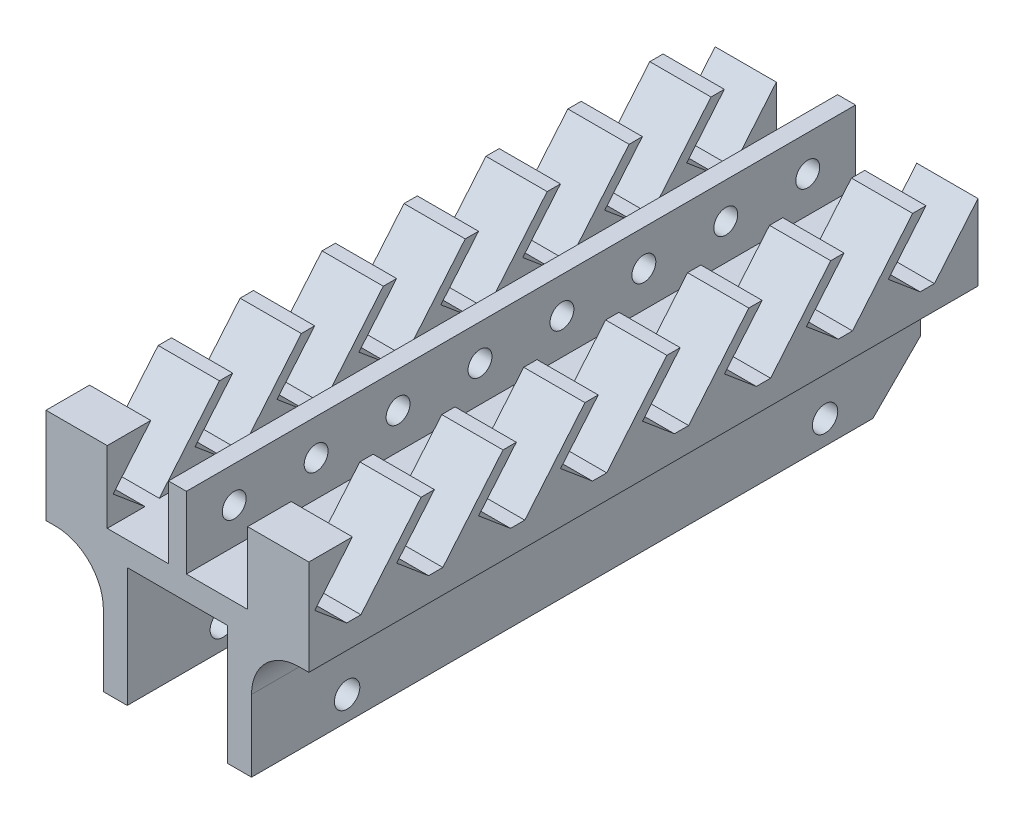
SolidWorks part; units mm, degrees
ref_plane "Front Plane" through (0, 0, 0) normal (0, 0, 1) x (1, 0, 0)
ref_plane "Top Plane" through (0, 0, 0) normal (0, 1, 0) x (1, 0, 0)
ref_plane "Right Plane" through (0, 0, 0) normal (1, 0, 0) x (0, 0, -1)
sketch "Sketch1" plane through (0, 0, 0) normal (0, 0, 1) x (1, 0, 0)
  line L0 (-19.685, 22.225) -> (19.685, 22.225)
  line L1 (-13.335, 15.875) -> (13.335, 15.875)
  line L2 (-13.335, 15.875) -> (-13.335, -15.875)
  line L4 (13.335, 15.875) -> (13.335, -15.875)
  line L5 (-13.335, 15.875) -> (13.335, -15.875) construction
  line L6 (-13.335, -15.875) -> (13.335, 15.875) construction
  line L10 (-19.685, -22.225) -> (19.685, -22.225) construction
  line L11 (-13.335, -15.875) -> (13.335, -15.875) construction
  line L12 (-19.685, 22.225) -> (-19.685, -22.225) construction
  line L13 (-19.685, 22.225) -> (-19.685, -15.875)
  line L14 (-19.685, -15.875) -> (-13.335, -15.875)
  line L15 (19.685, 22.225) -> (19.685, -15.875)
  line L16 (19.685, 22.225) -> (19.685, -22.225) construction
  line L17 (19.685, -15.875) -> (13.335, -15.875)
  point P0 (0, 0)
  dimension "D2" = 26.67
  dimension "D3" = 31.75
  dimension "D1" = 6.35
extrude "Boss-Extrude1" add sketch "Sketch1" along normal mid plane 177.8
hole_wizard "1/4 Clearance Hole1" positions "Sketch2" profile "Sketch3" hole size "1/4" standard "ANSI Inch" end condition through all
sketch "Sketch2" plane through (19.685, 0, 0) normal (1, 0, 0) x (0, 0, -1)
  line L0 (-88.9, -15.875) -> (88.9, -15.875) construction
  line L1 (-63.5, -9.525) -> (63.5, -9.525)
  point P0 (-63.5, -9.525)
  point P9 (63.5, -9.525)
  point P16 (0, -9.525)
  dimension "D1" = 6.35
  dimension "D2" = 127
sketch "Sketch3" plane through (19.685, -9.525, 63.5) normal (0, 1, 0) x (0, 0, -1)
  line L0 (0, 0) -> (0, 39.37)
  line L1 (0, 39.37) -> (3.3782, 39.37)
  line L2 (3.3782, 39.37) -> (3.3782, 0)
  line L5 (3.3782, 0) -> (0, 0)
  line L11 (0, -6.35) -> (0, 107.95) construction
  dimension "Thru Hole Dia." = 6.7564
  dimension "Thru Hole Depth" = 39.37
chamfer "Chamfer1" distance 12.7 angle 45 2 edges at (16.51, -15.875, -88.9) (-16.51, -15.875, -88.9)
sketch "Sketch8" plane through (0, 22.225, 0) normal (0, 1, 0) x (1, 0, 0)
  line L0 (19.685, -88.9) -> (-19.685, -88.9) construction
  line L1 (-34.925, 88.9) -> (34.925, 88.9)
  line L2 (-34.925, 88.9) -> (-34.925, -88.9)
  line L3 (-34.925, -88.9) -> (34.925, -88.9)
  line L4 (34.925, 88.9) -> (34.925, -88.9)
  line L5 (-34.925, 88.9) -> (34.925, -88.9) construction
  line L6 (-34.925, -88.9) -> (34.925, 88.9) construction
  point P0 (0, 0)
  dimension "D1" = 69.85
extrude "Boss-Extrude4" add sketch "Sketch8" against normal up to surface (6.35 mm away) up to face at (0, 15.875, 0)
sketch "Sketch4" plane through (0, 0, 0) normal (1, 0, 0) x (0, 0, -1)
  line L0 (-88.9, -15.875) -> (-88.9, 15.875) construction
  line L7 (-88.9, 22.225) -> (88.9, 22.225)
  line L11 (-88.9, 22.225) -> (-88.9, 41.275)
  line L12 (-88.9, 41.275) -> (88.9, 41.275)
  line L14 (88.9, 22.225) -> (88.9, 41.275)
  line L17 (88.9, -3.175) -> (88.9, 15.875) construction
  line L18 (-88.9, 22.225) -> (88.9, 22.225) construction
  dimension "D1" = 19.05
extrude "Boss-Extrude2" add sketch "Sketch4" along direction (-1, 0, 0) on the side of the normal mid plane 4.7625
hole_wizard "#12 Clearance Hole1" [suppressed] positions "Sketch6" profile "Sketch7" hole size "#12" standard "ANSI Inch"
sketch "Sketch6" [suppressed] plane through (-19.685, 0, 0) normal (-1, 0, 0) x (0, 0, 1)
  arc A0 (-12.7, 44.45) -> (0, 31.75) centre (-12.7, 31.75) ccw construction
  arc A1 (88.9, 34.925) -> (76.2, 47.625) centre (76.2, 34.925) ccw construction
  point P0 (-12.7, 31.75)
  point P2 (76.2, 34.925)
sketch "Sketch7" plane through (-19.685, 31.75, -12.7) normal (0, 1, 0) x (0, 0, 1)
  line L0 (0, 0) -> (0, 51.435)
  line L1 (0, 51.435) -> (2.8956, 51.435)
  line L2 (2.8956, 51.435) -> (2.8956, 0)
  line L5 (2.8956, 0) -> (0, 0)
  line L11 (0, -6.35) -> (0, 107.95) construction
  dimension "Thru Hole Dia." = 5.7912
  dimension "Thru Hole Depth" = 51.435
sketch "Sketch9" [suppressed] plane through (31.75, 0, 0) normal (1, 0, 0) x (0, 0, -1)
  line L0 (-88.9, 15.875) -> (-88.9, 22.225) construction
  line L1 (-88.9, 39.37) -> (88.9, 39.37)
  line L2 (-88.9, 39.37) -> (-88.9, 22.225)
  line L3 (-88.9, 22.225) -> (88.9, 22.225)
  line L4 (88.9, 39.37) -> (88.9, 22.225)
  line L5 (-88.9, 39.37) -> (88.9, 22.225) construction
  line L6 (-88.9, 22.225) -> (88.9, 39.37) construction
  point P0 (0, 30.7975)
  dimension "D1" = 17.145
extrude "Boss-Extrude5" [suppressed] add sketch "Sketch9" against normal blind 4.7625
fillet "Fillet2" [suppressed] radius 12.7
hole_wizard "#12 Clearance Hole2" [suppressed] positions "Sketch10" profile "Sketch11" hole size "#12" standard "ANSI Inch"
sketch "Sketch10" [suppressed] plane through (19.685, 0, 0) normal (1, 0, 0) x (0, 0, -1)
  line L0 (-25.4, 28.575) -> (12.7, 28.575)
  line L2 (-88.9, 15.875) -> (88.9, 15.875) construction
  line L3 (-63.5, 28.575) -> (-25.4, 28.575)
  line L5 (12.7, 28.575) -> (50.8, 28.575)
  line L12 (-88.9, 37.465) -> (-88.9, 22.225) construction
  point P0 (-25.4, 28.575)
  point P2 (12.7, 28.575)
  point P16 (-63.5, 28.575)
  point P27 (50.8, 28.575)
  point P58 (-44.45, 28.575)
  point P65 (-6.35, 28.575)
  point P66 (31.75, 28.575)
  point P67 (69.85, 28.575)
  dimension "D1" = 38.1
  dimension "D2" = 12.7
  dimension "D3" = 25.4
  dimension "D4" = 4
sketch "Sketch11" plane through (19.685, 28.575, 25.4) normal (0, 1, 0) x (0, 0, -1)
  line L0 (0, 0) -> (0, 51.435)
  line L1 (0, 51.435) -> (2.8956, 51.435)
  line L2 (2.8956, 51.435) -> (2.8956, 0)
  line L5 (2.8956, 0) -> (0, 0)
  line L11 (0, -6.35) -> (0, 107.95) construction
  dimension "Thru Hole Dia." = 5.7912
  dimension "Thru Hole Depth" = 51.435
sketch "Sketch23" plane through (-2.3813, 0, 0) normal (-1, 0, 0) x (0, 0, 1)
  line L2 (88.9, -15.875) -> (88.9, 15.875) construction
  line L3 (88.9, 41.275) -> (88.9, 22.225) construction
  line L4 (-88.9, 22.225) -> (-88.9, 41.275) construction
  point P0 (88.9, 31.75)
  point P1 (76.2, 31.75)
  point P39 (54.4286, 31.75)
  point P40 (32.6571, 31.75)
  point P41 (10.8857, 31.75)
  point P42 (-10.8857, 31.75)
  point P43 (-32.6571, 31.75)
  point P44 (-54.4286, 31.75)
  point P45 (-76.2, 31.75)
  dimension "D1" = 12.7
  dimension "D3" = 12.7
  dimension "D2" = 8
hole_wizard "1/4 (0.25) Diameter Hole1" positions "Sketch23" profile "Sketch24" hole size "1/4" standard "ANSI Inch"
sketch "Sketch24" plane through (-2.3813, 31.75, -76.2) normal (0, 1, 0) x (0, 0, 1)
  line L0 (0, 0) -> (0, 13.8457)
  line L1 (0, 13.8457) -> (3.175, 11.938)
  line L2 (3.175, 11.938) -> (3.175, 0)
  line L5 (3.175, 0) -> (0, 0)
  line L10 (0, 13.8457) -> (-3.175, 11.938) construction
  line L11 (0, -6.35) -> (0, 107.95) construction
  dimension "Hole Dia." = 6.35
  dimension "Hole Depth" = 11.938
  dimension "Drill Angle" = 118
sketch "Sketch22" plane through (0, 0, 0) normal (1, 0, 0) x (0, 0, -1)
  line L0 (0, 40.2144) -> (0, -22.5999) construction
sketch "Sketch28" plane through (0, 22.225, 0) normal (0, 1, 0) x (1, 0, 0)
  line L0 (2.3813, -88.9) -> (2.3813, 88.9) construction
  line L1 (-2.3813, -88.9) -> (-2.3813, 88.9) construction
  line L2 (2.3813, -88.9) -> (2.3813, 88.9)
  line L3 (-2.3813, -88.9) -> (-2.3813, 88.9)
  line L4 (-2.3813, -76.2) -> (2.3813, -76.2) construction
  line L5 (0, -82.931) -> (0, -69.469) construction
  line L6 (-34.925, -69.469) -> (34.925, -69.469)
  line L7 (34.925, -88.9) -> (34.925, 88.9) construction
  line L8 (-34.925, -82.931) -> (34.925, -82.931)
  line L9 (-34.925, -61.1596) -> (34.925, -61.1596)
  line L10 (-34.925, -47.6976) -> (34.925, -47.6976)
  line L11 (-34.925, -39.3881) -> (34.925, -39.3881)
  line L12 (-34.925, -25.9261) -> (34.925, -25.9261)
  line L13 (-34.925, -17.6167) -> (34.925, -17.6167)
  line L14 (-34.925, -4.1547) -> (34.925, -4.1547)
  line L15 (-34.925, 4.1547) -> (34.925, 4.1547)
  line L16 (-34.925, 17.6167) -> (34.925, 17.6167)
  line L17 (-34.925, 25.9261) -> (34.925, 25.9261)
  line L18 (-34.925, 39.3881) -> (34.925, 39.3881)
  line L19 (-34.925, 47.6976) -> (34.925, 47.6976)
  line L20 (-34.925, 61.1596) -> (34.925, 61.1596)
  line L21 (-34.925, 69.469) -> (34.925, 69.469)
  line L22 (-34.925, 82.931) -> (34.925, 82.931)
  line L23 (-2.3813, 69.469) -> (-2.3813, 82.931)
  line L24 (-34.925, 88.9) -> (-34.925, -88.9) construction
  line L25 (-34.925, 88.9) -> (-34.925, -88.9)
  line L26 (34.925, -88.9) -> (34.925, 88.9)
  line L27 (34.925, -88.9) -> (2.3813, -88.9) construction
  line L28 (-2.3813, -88.9) -> (-34.925, -88.9) construction
  line L29 (-2.3813, 88.9) -> (-34.925, 88.9) construction
  line L30 (34.925, 88.9) -> (2.3813, 88.9) construction
  line L31 (34.925, -88.9) -> (2.3813, -88.9)
  line L32 (-2.3813, -88.9) -> (-34.925, -88.9)
  line L33 (-2.3813, 88.9) -> (-34.925, 88.9)
  line L34 (34.925, 88.9) -> (2.3813, 88.9)
  point P0 (-2.3813, -76.2)
  point P8 (-2.3813, 76.2)
  point P12 (0, -76.2)
  point P17 (0, -69.469)
  point P20 (0, -82.931)
  point P53 (-2.3813, 76.2)
  line M9 (2.3813, 88.9) -> (2.3813, -88.9)
  line M11 (34.925, -88.9) -> (34.925, 88.9)
  line M12 (34.925, 88.9) -> (2.3813, 88.9)
  dimension "D1" = 13.462
  dimension "D2" = 8
extrude "Boss-Extrude6" [suppressed] add sketch "Sketch28" along normal up to surface (19.05 mm away) contours L11 L2 L10 M11 | L11 L25 L10 L3 | L9 L25 L6 L3 | L13 L2 L12 M11 | L15 L2 L14 M11 | L15 L25 L14 L3 | L17 L25 L16 L3 | L19 L2 L18 M11 | L19 L25 L18 L3 | L21 L2 L20 M11 | L32 L3 L8 L25 | L22 M9 M11 M12
fillet "Fillet3" radius 12.7 2 edges at (19.685, 15.875, 0) (-19.685, 15.875, 0)
sketch "Sketch30" plane through (0, 0, 0) normal (1, 0, 0) x (0, 0, -1)
  line L0 (-81.5508, 36.2399) -> (-70.8492, 27.2601) construction
  line L1 (-88.9, 22.225) -> (88.9, 22.225) construction
  line L2 (-88.9, 22.225) -> (88.9, 22.225)
  line L3 (-75.0742, 22.225) -> (-59.0893, 41.275)
  line L4 (88.9, 41.275) -> (-88.9, 41.275) construction
  line L5 (88.9, 41.275) -> (-88.9, 41.275)
  line L6 (-77.3258, 41.275) -> (-88.9, 27.4815)
  line L7 (-88.9, 41.275) -> (-88.9, 22.225) construction
  line L8 (-88.9, 41.275) -> (-88.9, 22.225)
  line L9 (-75.0742, 22.225) -> (-85.7758, 31.2047) construction
  line L10 (-55.5544, 41.275) -> (-71.5393, 22.225)
  line L11 (-59.7794, 36.2399) -> (-49.0778, 27.2601) construction
  line L12 (-53.3027, 22.225) -> (-37.3179, 41.275)
  line L13 (-33.783, 41.275) -> (-49.7678, 22.225)
  line L14 (-38.008, 36.2399) -> (-27.3063, 27.2601) construction
  line L15 (-31.5313, 22.225) -> (-15.5464, 41.275)
  line L16 (-12.0116, 41.275) -> (-27.9964, 22.225)
  line L17 (-16.2365, 36.2399) -> (-5.5349, 27.2601) construction
  line L18 (-9.7599, 22.225) -> (6.225, 41.275)
  line L19 (9.7599, 41.275) -> (-6.225, 22.225)
  line L20 (5.5349, 36.2399) -> (16.2365, 27.2601) construction
  line L21 (12.0116, 22.225) -> (27.9964, 41.275)
  line L22 (31.5313, 41.275) -> (15.5464, 22.225)
  line L23 (27.3063, 36.2399) -> (38.008, 27.2601) construction
  line L24 (33.783, 22.225) -> (49.7678, 41.275)
  line L25 (53.3027, 41.275) -> (37.3179, 22.225)
  line L26 (49.0778, 36.2399) -> (59.7794, 27.2601) construction
  line L27 (55.5544, 22.225) -> (71.5393, 41.275)
  line L28 (75.0742, 41.275) -> (59.0893, 22.225)
  line L29 (70.8492, 36.2399) -> (81.5508, 27.2601) construction
  line L30 (77.3258, 22.225) -> (88.9, 36.0185)
  line L31 (88.9, 22.225) -> (88.9, 41.275) construction
  line L32 (88.9, 22.225) -> (88.9, 41.275)
  line L33 (-87.3379, 29.3431) -> (-78.8549, 22.225)
  line L34 (-86.5785, 25.5335) -> (-83.4543, 29.2568) construction
  line L35 (-86.5785, 25.5335) -> (-88.9, 27.4815) construction
  line L36 (-65.5665, 29.3431) -> (-57.0834, 22.225)
  line L37 (-43.795, 29.3431) -> (-35.312, 22.225)
  line L38 (-22.0236, 29.3431) -> (-13.5406, 22.225)
  line L39 (-0.2522, 29.3431) -> (8.2308, 22.225)
  line L40 (21.5192, 29.3431) -> (30.0023, 22.225)
  line L41 (43.2907, 29.3431) -> (51.7737, 22.225)
  line L42 (65.0621, 29.3431) -> (73.5451, 22.225)
  point P5 (-76.2, 31.75)
  point P61 (-85.0164, 27.3951)
  dimension "D1" = 40
  dimension "D2" = 13.97
  dimension "D3" = 8
  dimension "D4" = 8
extrude "Boss-Extrude7" add sketch "Sketch30" along normal mid plane 69.85 contours L5 L8 L6 | L10 L5 L3 L2 | L13 L5 L12 L2 | L16 L5 L15 L2 | L19 L5 L18 L2 | L22 L5 L21 L2 | L25 L5 L24 L2 | L28 L5 L27 L2 | L33 L6 L8 L2 | L36 L10 L2 | L37 L13 L2 | L38 L16 L2 | L39 L19 L2 | L40 L22 L2 | L41 L25 L2 | L42 L28 L2 | L2 L32 L30
sketch "Sketch31" plane through (0, 0, 88.9) normal (0, 0, 1) x (1, 0, 0)
  line L0 (34.925, 41.275) -> (2.3813, 41.275) construction
  line L1 (34.925, 41.275) -> (2.3813, 41.275)
  line L2 (34.925, 22.225) -> (2.3813, 22.225) construction
  line L3 (2.3813, 41.275) -> (18.6531, 41.275)
  line L4 (2.3813, 41.275) -> (2.3813, 22.225)
  line L5 (2.3813, 22.225) -> (18.6531, 22.225)
  line L6 (18.6531, 41.275) -> (18.6531, 22.225)
  line L7 (0, -31.4325) -> (0, 31.4325) construction
  line L8 (-18.6531, 41.275) -> (-18.6531, 22.225)
  line L9 (-2.3813, 22.225) -> (-18.6531, 22.225)
  line L10 (-2.3813, 41.275) -> (-2.3813, 22.225)
  line L11 (-2.3813, 41.275) -> (-18.6531, 41.275)
  point P5 (0, 0)
  line M4 (34.925, 41.275) -> (-34.925, 41.275)
extrude "Cut-Extrude1" cut sketch "Sketch31" against normal through all contours L6 L1 L4 L5 | L10 L8 L9 M4
